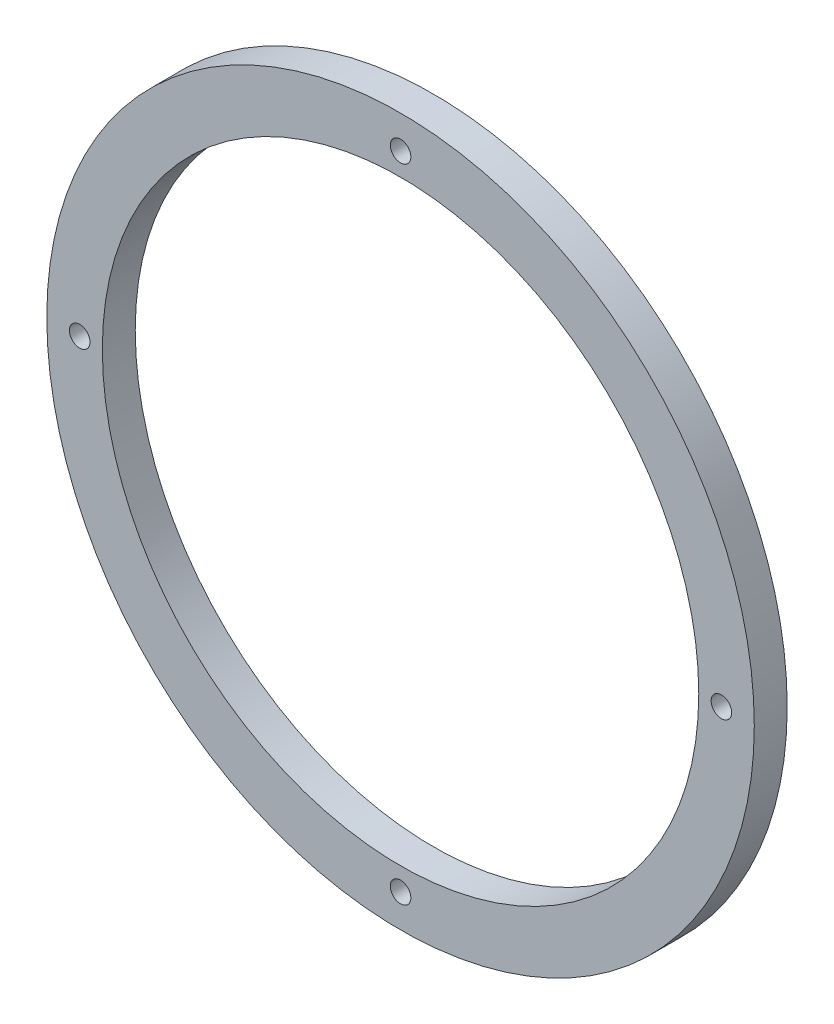
SolidWorks part; units mm, degrees
ref_plane "Front Plane" through (0, 0, 0) normal (0, 0, 1) x (1, 0, 0)
ref_plane "Top Plane" through (0, 0, 0) normal (0, 1, 0) x (1, 0, 0)
ref_plane "Right Plane" through (0, 0, 0) normal (1, 0, 0) x (0, 0, -1)
sketch "Sketch1" plane through (0, 0, 0) normal (0, 0, 1) x (1, 0, 0)
  circle A0 centre (0, 0) radius 72.5
  circle A1 centre (0, 0) radius 86
  circle A2 centre (0, 78) radius 2.5
  circle A3 centre (78, 0) radius 2.5
  circle A4 centre (0, -78) radius 2.5
  circle A5 centre (-78, 0) radius 2.5
  point P6 (-116.263, -17.128)
  point P7 (0, 0)
  point P15 (0, 0)
  dimension "D1" = 172
  dimension "D2" = 145
  dimension "D4" = 5
  dimension "D3" = 78
  dimension "D5" = 4
extrude "Boss-Extrude1" add sketch "Sketch1" along normal blind 8
